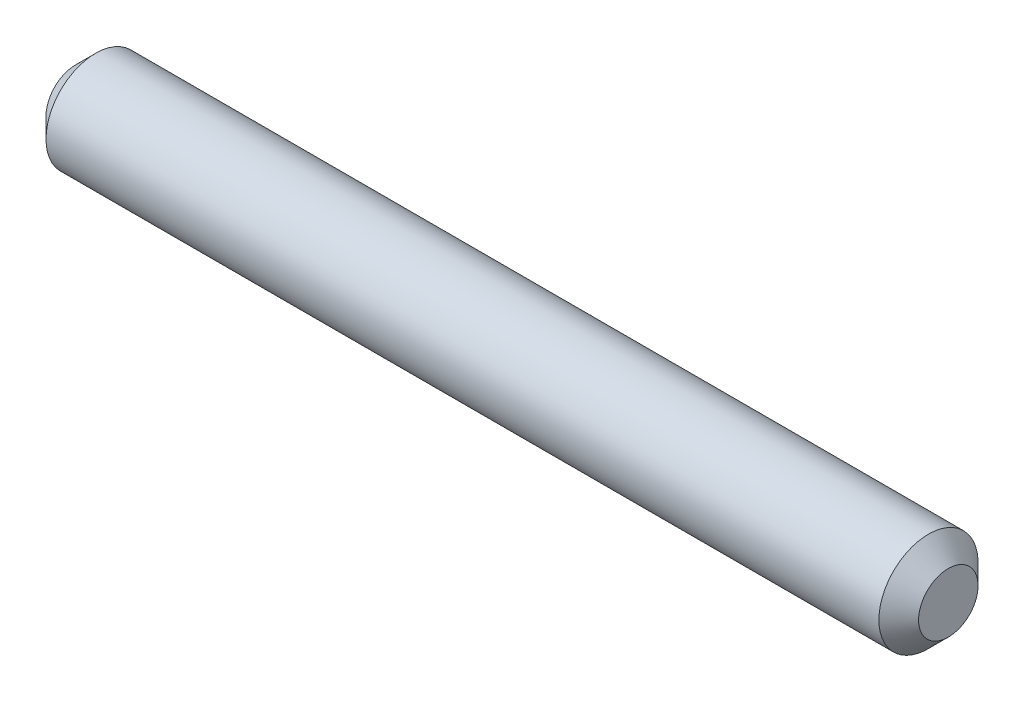
SolidWorks part; units mm, degrees
ref_plane "Front Plane" through (0, 0, 0) normal (0, 0, 1) x (1, 0, 0)
ref_plane "Top Plane" through (0, 0, 0) normal (0, 1, 0) x (1, 0, 0)
ref_plane "Right Plane" through (0, 0, 0) normal (1, 0, 0) x (0, 0, -1)
sketch "Sketch2" plane through (0, 0, 0) normal (0, 0, 1) x (1, 0, 0)
  line L0 (0, 1.5) -> (1, 2.5)
  line L1 (0, 0) -> (44, 0)
  line L2 (0, 0) -> (0, 1.5)
  line L3 (1, 2.5) -> (43, 2.5)
  line L4 (44, 0) -> (44, 1.5)
  line L5 (43, 2.5) -> (44, 1.5)
  point P1 (44, 2.5)
  point P2 (0, 2.5)
  dimension "D1" = 44
  dimension "D2" = 2.5
revolve "Revolve1" add sketch "Sketch2" angle 360 about L1
